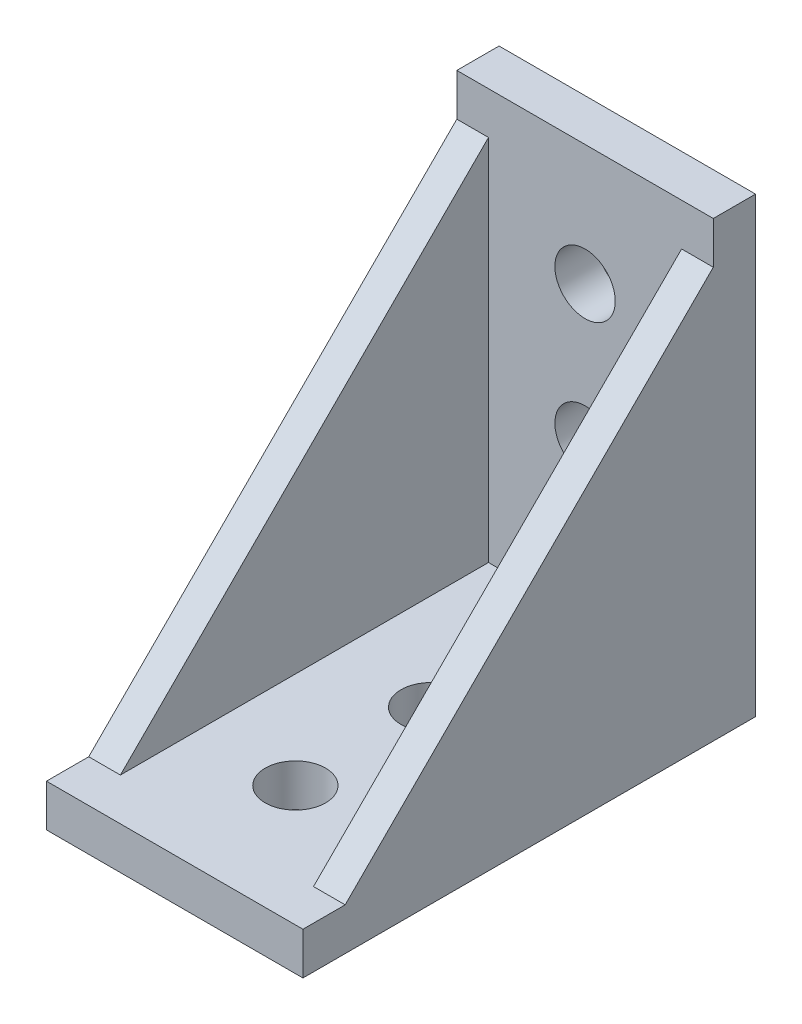
SolidWorks part; units mm, degrees
material "聚脂树脂"
ref_plane "前视基准面" through (0, 0, 0) normal (0, 0, 1) x (1, 0, 0)
ref_plane "上视基准面" through (0, 0, 0) normal (0, 1, 0) x (1, 0, 0)
ref_plane "右视基准面" through (0, 0, 0) normal (1, 0, 0) x (0, 0, -1)
other "Configuration Table"
sketch "草图1" plane through (0, 0, 0) normal (1, 0, 0) x (0, 0, -1)
  line L0 (0, 0) -> (-30, 0)
  line L1 (-30, 0) -> (-30, 2.8)
  line L3 (-2.8, 30) -> (0, 30)
  line L4 (0, 30) -> (0, 0)
  line L5 (-30, 2.8) -> (-27.2, 2.8)
  line L6 (-27.2, 2.8) -> (-2.8, 27.2)
  line L7 (-2.8, 27.2) -> (-2.8, 30)
  dimension "D1" = 2.8
  dimension "D2" = 2.8
  dimension "D3" = 30
extrude "凸台-拉伸1" add sketch "草图1" along normal blind 17
sketch "草图2" plane through (0, 0, 0) normal (0, 1, 0) x (1, 0, 0)
  line L1 (2.1, -2.8) -> (14.9, -2.8)
  line L2 (2.1, -2.8) -> (2.1, -27.2)
  line L3 (2.1, -27.2) -> (14.9, -27.2)
  line L4 (14.9, -2.8) -> (14.9, -27.2)
  line L6 (17, -27.2) -> (0, -27.2) construction
  line L7 (17, -2.8) -> (0, -2.8) construction
  line L10 (8.5, 9.2994) -> (8.5, -33.0479) construction
  line L11 (17, 0) -> (0, 0) construction
  point P12 (8.5, 0)
  dimension "D1" = 2.1
extrude "切除-拉伸1" cut sketch "草图2" against normal up to surface (27.2 mm away) from surface at 30 up to face at (8.5, 2.8, 28.6) starting at face at (8.5, 30, 1.4)
sketch "草图3" plane through (0, 0, 0) normal (0, 1, 0) x (1, 0, 0)
  line L0 (8.5, 4.9951) -> (8.5, -32.7845) construction
  line L4 (17, 0) -> (0, 0) construction
  line L5 (0, -30) -> (17, -30) construction
  circle A2 centre (8.5, -22) radius 2
  circle A3 centre (8.5, -13) radius 2
  point P6 (8.5, 0)
  dimension "D2" = 8
  dimension "D1" = 4
  dimension "D3" = 9
extrude "切除-拉伸2" cut sketch "草图3" along normal up to next
sketch "草图4" plane through (0, 0, 0) normal (0, 0, 1) x (1, 0, 0)
  line L0 (8.5, 28.1696) -> (8.5, -5.8506) construction
  line L4 (17, 0) -> (0, 0) construction
  line L5 (17, 30) -> (0, 30) construction
  circle A2 centre (8.5, 22) radius 2
  circle A3 centre (8.5, 13) radius 2
  point P6 (8.5, 0)
  dimension "D2" = 9
  dimension "D1" = 4
  dimension "D3" = 8
extrude "切除-拉伸3" cut sketch "草图4" along normal up to next
